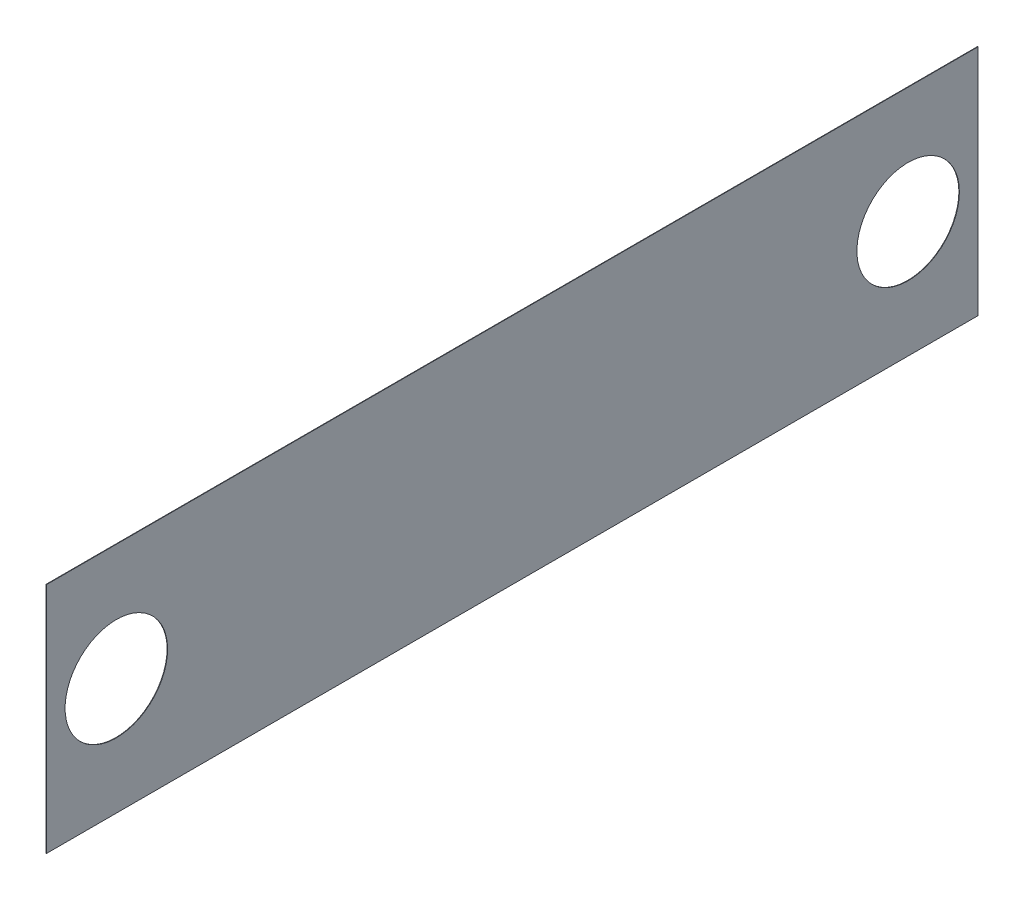
SolidWorks part; units mm, degrees
material "Low Carbon Steel"
ref_plane "Front Plane" through (0, 0, 0) normal (0, 0, 1) x (1, 0, 0)
ref_plane "Top Plane" through (0, 0, 0) normal (0, 1, 0) x (1, 0, 0)
ref_plane "Right Plane" through (0, 0, 0) normal (1, 0, 0) x (0, 0, -1)
sketch "Sketch1" plane through (0, 0, 0) normal (1, 0, 0) x (0, 0, -1)
  line L0 (-50, -12.5) -> (50, 12.5) construction
  line L1 (-50, 12.5) -> (50, 12.5)
  line L2 (-50, 12.5) -> (-50, -12.5)
  line L3 (-50, -12.5) -> (50, -12.5)
  line L4 (50, 12.5) -> (50, -12.5)
  dimension "D1" = 100
  dimension "D2" = 25
extrude "Boss-Extrude1" add sketch "Sketch1" along normal blind 0.0508
hole_wizard "M10 Clearance Hole1" positions "Sketch2" profile "Sketch3" hole size "M10" standard "Peddi DIN" end condition through all
sketch "Sketch2" plane through (0.0508, 0, 0) normal (1, 0, 0) x (0, 0, -1)
  line L0 (42.5, 0) -> (-42.5, 0) construction
  point P0 (-42.5, 0)
  point P2 (42.5, 0)
  dimension "D1" = 85
sketch "Sketch3" plane through (0.0508, 0, 42.5) normal (0, 1, 0) x (0, 0, -1)
  line L0 (0, 0) -> (0, 0.0508)
  line L1 (0, 0.0508) -> (5.5, 0.0508)
  line L2 (5.5, 0.0508) -> (5.5, 0)
  line L5 (5.5, 0) -> (0, 0)
  line L11 (0, -6.35) -> (0, 107.95) construction
  dimension "Thru Hole Dia." = 11
  dimension "Thru Hole Depth" = 0.0508
other "Freeze***"
